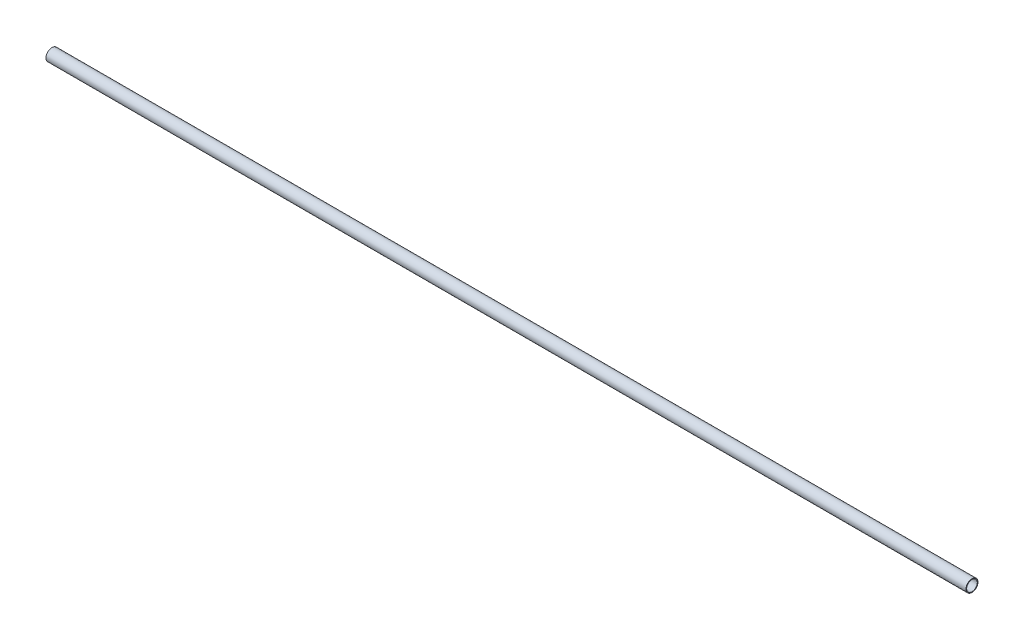
SolidWorks part; units mm, degrees
ref_plane "Front Plane" through (0, 0, 0) normal (0, 0, 1) x (1, 0, 0)
ref_plane "Top Plane" through (0, 0, 0) normal (0, 1, 0) x (1, 0, 0)
ref_plane "Right Plane" through (0, 0, 0) normal (1, 0, 0) x (0, 0, -1)
sketch "Sketch1" plane through (0, 0, 0) normal (0, 1, 0) x (1, 0, 0)
  line L0 (0, 0) -> (1371.6, 0)
  dimension "D1" = 1371.6
sketch "Sketch2" plane through (0, 0, 0) normal (1, 0, 0) x (0, 0, -1)
  circle A0 centre (0, 0) radius 7.8994
  circle A1 centre (0, 0) radius 8.9662
sweep "Sweep1" add profiles "Sketch2" path "Sketch1"
sketch "Sketch3" plane through (0, 0, 0) normal (1, 0, 0) x (0, 0, -1)
  point P0 (0, 0)
